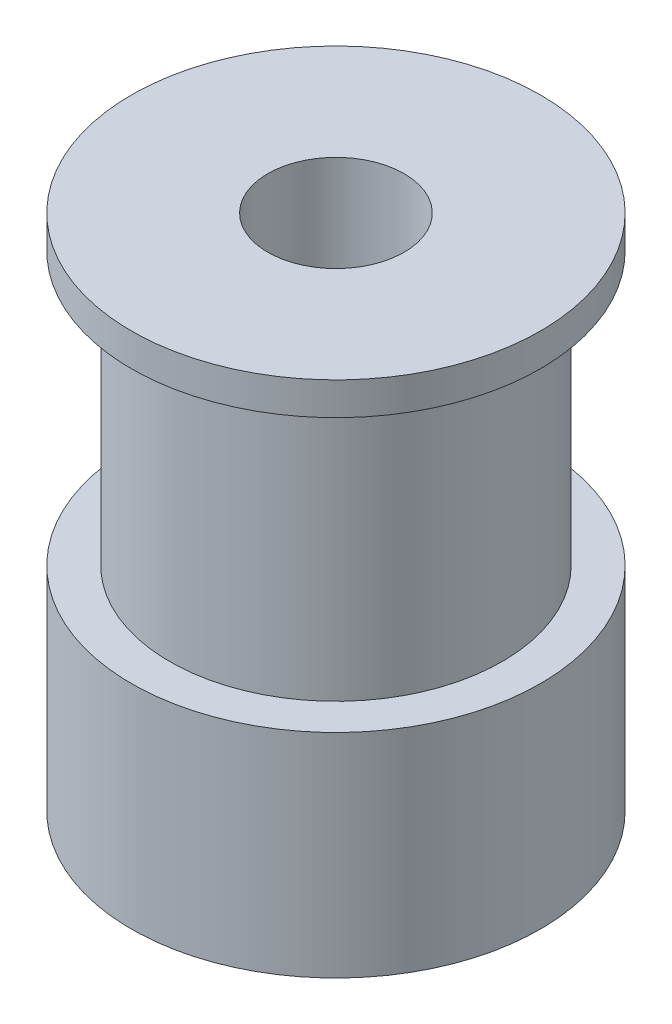
SolidWorks part; units mm, degrees
material "1060 Alloy"
ref_plane "Front Plane" through (0, 0, 0) normal (0, 0, 1) x (1, 0, 0)
ref_plane "Top Plane" through (0, 0, 0) normal (0, 1, 0) x (1, 0, 0)
ref_plane "Right Plane" through (0, 0, 0) normal (1, 0, 0) x (0, 0, -1)
sketch "Sketch1" plane through (0, 0, 0) normal (0, 0, 1) x (1, 0, 0)
  line L0 (0, 0) -> (0, 20.5621) construction
  line L1 (-2.5, 0) -> (-2.5, 19)
  line L2 (-2.5, 19) -> (-7.5, 19)
  line L3 (-7.5, 19) -> (-7.5, 17.8)
  line L4 (-7.5, 17.8) -> (-6.1, 17.8)
  line L5 (-6.1, 17.8) -> (-6.1, 7.8)
  line L6 (-6.1, 7.8) -> (-7.5, 7.8)
  line L7 (-7.5, 7.8) -> (-7.5, 0)
  line L8 (-7.5, 0) -> (-2.5, 0)
  line L9 (0, 0) -> (-12.3719, 0) construction
  dimension "D1" = 5
  dimension "D2" = 15
  dimension "D3" = 12.2
  dimension "D4" = 1.2
  dimension "D5" = 10
  dimension "D6" = 19
revolve "Revolve1" add sketch "Sketch1" angle 360 about L0
